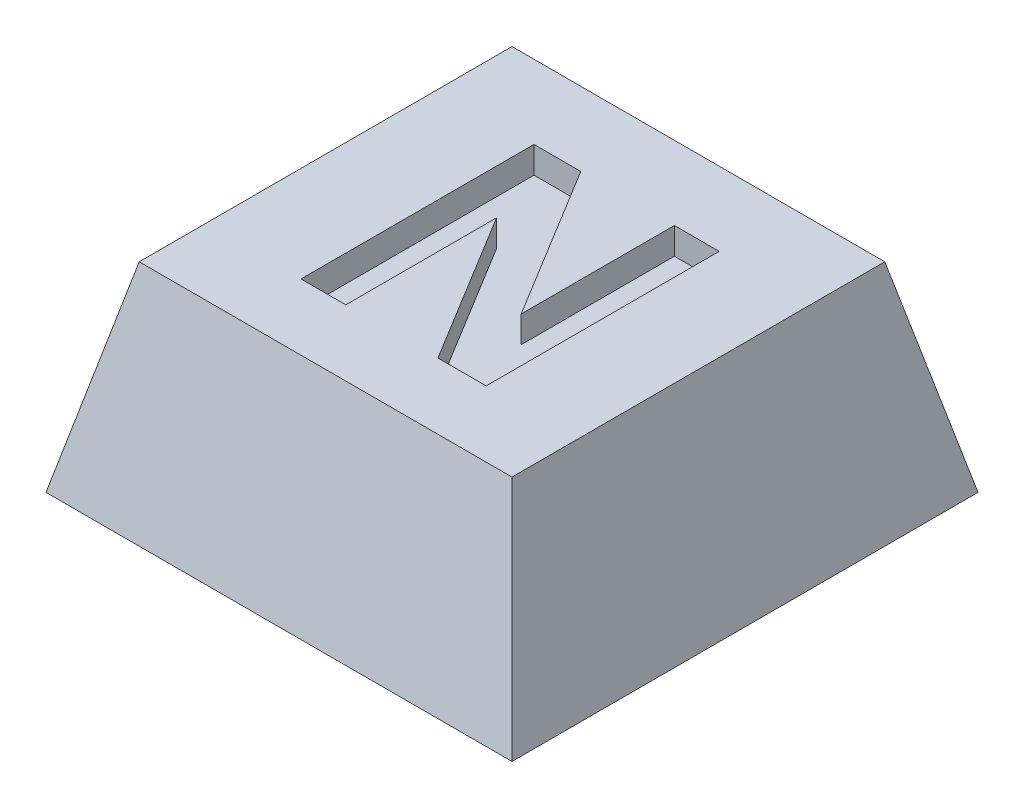
SolidWorks part; units mm, degrees
ref_plane "Front Plane" through (0, 0, 0) normal (0, 0, 1) x (1, 0, 0)
ref_plane "Top Plane" through (0, 0, 0) normal (0, 1, 0) x (1, 0, 0)
ref_plane "Right Plane" through (0, 0, 0) normal (1, 0, 0) x (0, 0, -1)
sketch "Sketch1" plane through (0, 0, 0) normal (0, 1, 0) x (1, 0, 0)
  line L1 (0, 0) -> (7, 0)
  line L2 (0, 0) -> (0, 7)
  line L3 (0, 7) -> (7, 7)
  line L4 (7, 0) -> (7, 7)
  dimension "D1" = 7
  dimension "D2" = 7
extrude "Boss-Extrude1" add sketch "Sketch1" along normal blind 3
sketch "Sketch2" plane through (0, 0, 0) normal (0, 0, 1) x (1, 0, 0)
  line L0 (0, 0) -> (0.7, 3)
  line L1 (0, 3) -> (7, 3) construction
  line L2 (0.7, 3) -> (0, 3)
  line L3 (0, 3) -> (0, 0)
  line L4 (7, 0) -> (6.3, 3)
  line L5 (6.3, 3) -> (7, 3)
  line L6 (7, 3) -> (7, 0)
  dimension "D1" = 0.7
  dimension "D2" = 0.7
extrude "Cut-Extrude1" cut sketch "Sketch2" against normal blind 7
sketch "Sketch3" plane through (0, 0, 0) normal (1, 0, 0) x (0, 0, -1)
  line L0 (0, 0) -> (0.7, 3)
  line L1 (7, 3) -> (0, 3) construction
  line L2 (0.7, 3) -> (0, 3)
  line L3 (0, 3) -> (0, 0)
  line L4 (7, 3) -> (6.3, 3)
  line L5 (6.3, 3) -> (7, 0)
  line L6 (7, 3) -> (7, 0)
  dimension "D1" = 0.7
  dimension "D2" = 0.7
extrude "Cut-Extrude2" cut sketch "Sketch3" along normal blind 11
sketch "Sketch4" plane through (0, 0, 0) normal (0, -1, 0) x (1, 0, 0)
  line L0 (3.5, 0) -> (3.5, -7) construction
  line L1 (0, 0) -> (7, 0) construction
  line L2 (7, -7) -> (0, -7) construction
  line L3 (0, -3.5) -> (7, -3.5) construction
  line L4 (0, -7) -> (0, 0) construction
  line L5 (7, 0) -> (7, -7) construction
  circle A0 centre (3.5, -3.5) radius 1.8
  dimension "D1" = 3.6
extrude "Cut-Extrude3" cut sketch "Sketch4" against normal blind 0.8
sketch "Sketch5" plane through (0, 3, 0) normal (0, 1, 0) x (1, 0, 0)
  text T0 "N" font "Arial" height 3.5
extrude "Cut-Extrude4" cut sketch "Sketch5" against normal blind 0.4
